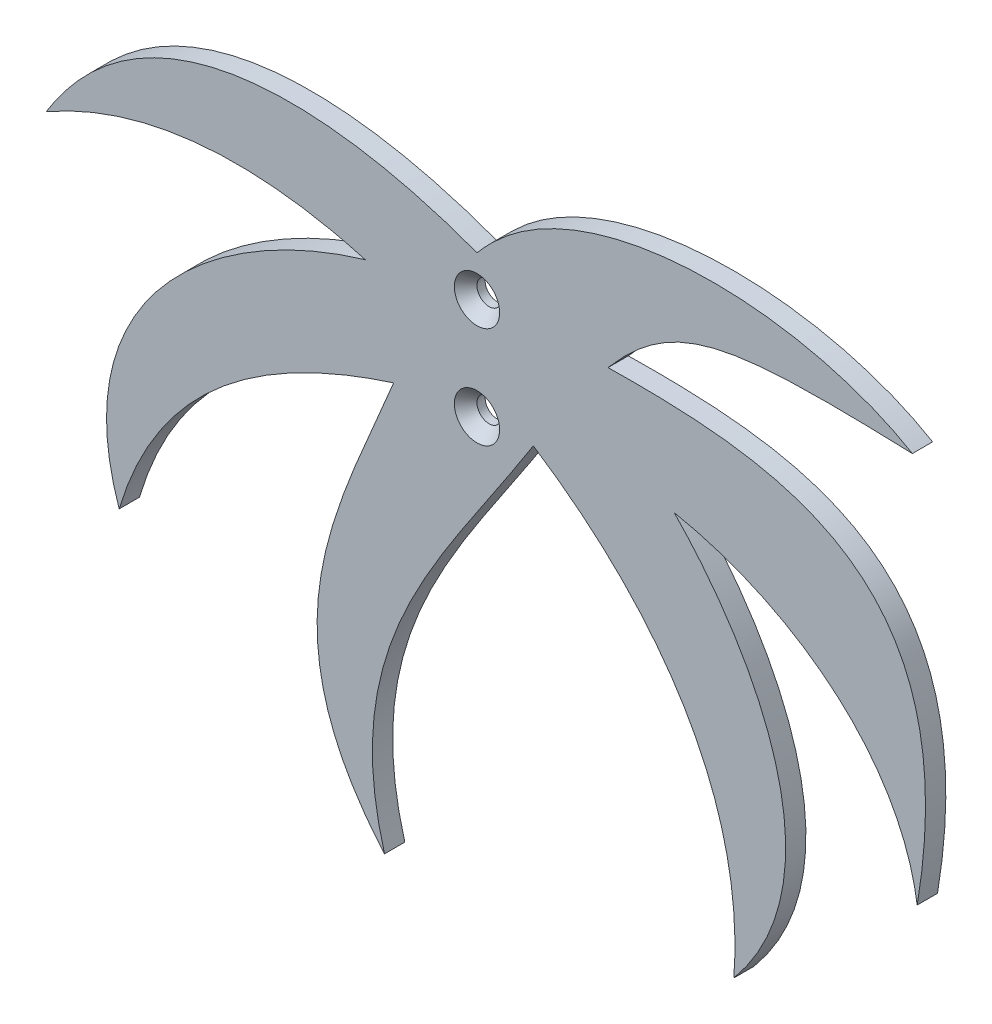
SolidWorks part; units mm, degrees
ref_plane "Front Plane" through (0, 0, 0) normal (0, 0, 1) x (1, 0, 0)
ref_plane "Top Plane" through (0, 0, 0) normal (0, 1, 0) x (1, 0, 0)
ref_plane "Right Plane" through (0, 0, 0) normal (1, 0, 0) x (0, 0, -1)
sketch "Sketch1" plane through (0, 0, 0) normal (0, 0, 1) x (1, 0, 0)
  line L0 (216.6667, 690.5) -> (1083.3333, 690.5) construction
  spline S0 degree 3 poles (34.9319, 165.0254) (48.8281, 187.7197) (76.4544, 188.5201) (100.4458, 180.333) (102.3548, 179.6133) knots 0 0 0 0 0.389678 0.423902 0.423902 0.423902 0.423902
  spline S1 degree 3 poles (34.9319, 165.0254) (50.9354, 174.1809) (68.38, 174.6273) (84.8832, 169.9282) knots 0 0 0 0 0.348653 0.348653 0.348653 0.348653
  spline S2 degree 3 poles (46.3484, 116.89) (37.8919, 141.3966) (59.9186, 161.5978) (82.9281, 169.3503) (84.8832, 169.9282) knots 0 0 0 0 0.348685 0.380913 0.380913 0.380913 0.380913
  spline S3 degree 3 poles (46.3484, 116.89) (52.7964, 138.6162) (70.0851, 149.2983) (89.3085, 155.4556) knots 0 0 0 0 0.378548 0.378548 0.378548 0.378548
  spline S4 degree 3 poles (87.8818, 90.9031) (69.285, 112.2089) (79.6869, 132.5367) (88.8589, 154.3861) (89.3085, 155.4556) knots 0 0 0 0 0.384997 0.404814 0.404814 0.404814 0.404814
  spline S5 degree 3 poles (87.8818, 90.9031) (80.7441, 115.7297) (96.5015, 135.0011) (109.9674, 155.9858) (111.169, 157.8511) knots 0 0 0 0 0.464689 0.510269 0.510269 0.510269 0.510269
  spline S6 degree 3 poles (133.2112, 159.8318) (135.1711, 157.8218) (149.4116, 141.4919) (156.6773, 118.334) (142.5422, 101.4104) knots 0.63299 0.63299 0.63299 0.63299 0.680759 1 1 1 1
  spline S7 degree 3 poles (111.169, 157.8511) (130.2813, 145.4166) (144.4934, 126.3327) (142.5422, 101.4104) knots 0.543056 0.543056 0.543056 0.543056 1 1 1 1
  spline S8 degree 3 poles (102.3548, 179.6133) (103.6883, 181.1888) (120.0852, 197.822) (153.7251, 196.4236) (170.4913, 186.4679) knots 0.566671 0.566671 0.566671 0.566671 0.604774 1 1 1 1
  spline S9 degree 3 poles (133.2112, 159.8318) (133.9795, 159.6828) (151.702, 155.882) (168.6187, 143.5623) (171.2533, 125.6539) knots 0.658819 0.658819 0.658819 0.658819 0.673583 1 1 1 1
  spline S10 degree 3 poles (122.8545, 174.3046) (133.2177, 186.4209) (141.874, 187.4378) (170.4913, 186.4679) knots 0.652056 0.652056 0.652056 0.652056 1 1 1 1
  spline S11 degree 3 poles (122.8545, 174.3046) (150.1009, 174.692) (179.0765, 172.111) (171.2533, 125.6539) knots 0.582619 0.582619 0.582619 0.582619 1 1 1 1
  point P9 (124.3092, 175.9512)
  point P12 (124.3092, 175.9512)
  dimension "D1" = 34.9319
  dimension "D2" = 46.3484
  dimension "D3" = 47.8726
  dimension "D4" = 60.6781
  dimension "D5" = 67.6104
  dimension "D6" = 68.622
  dimension "D7" = 77.8985
  dimension "D8" = 79.0416
  dimension "D9" = 87.8818
  dimension "D10" = 87.958
  dimension "D11" = 89.4821
  dimension "D12" = 84.8832
  dimension "D13" = 96.5482
  dimension "D14" = 89.3085
  dimension "D15" = 102.3548
  dimension "D16" = 107.5434
  dimension "D17" = 106.7052
  dimension "D18" = 111.169
  dimension "D19" = 122.8545
  dimension "D20" = 124.2805
  dimension "D21" = 131.2441
  dimension "D22" = 132.2348
  dimension "D23" = 142.5422
  dimension "D24" = 133.2112
  dimension "D25" = 135.5118
  dimension "D26" = 138.76
  dimension "D27" = 170.4913
  dimension "D28" = 171.2533
  dimension "D29" = 90.9031
  dimension "D30" = 101.4104
  dimension "D31" = 116.89
  dimension "D32" = 121.6149
  dimension "D33" = 123.5201
  dimension "D34" = 125.6539
  dimension "D35" = 150.2543
  dimension "D36" = 151.8203
  dimension "D37" = 142.5721
  dimension "D38" = 145.3918
  dimension "D39" = 152.2505
  dimension "D40" = 163.7087
  dimension "D41" = 128.4849
  dimension "D42" = 138.1521
  dimension "D43" = 153.4552
  dimension "D44" = 165.0254
  dimension "D45" = 167.9494
  dimension "D46" = 155.4556
  dimension "D47" = 172.7543
  dimension "D48" = 157.8511
  dimension "D49" = 159.3379
  dimension "D50" = 181.5964
  dimension "D51" = 183.9745
  dimension "D52" = 186.4679
  dimension "D53" = 159.8318
  dimension "D54" = 690.5
  dimension "D55" = 169.9282
  dimension "D56" = 171.455
  dimension "D57" = 174.3046
  dimension "D58" = 175.9121
  dimension "D59" = 179.6133
  dimension "D60" = 193.6315
extrude "Boss-Extrude1" add sketch "Sketch1" along normal blind 3.175
hole_wizard "CSK for #6 Flat Head Machine Screw1" positions "Sketch2" profile "Sketch3" countersink size "#6" standard "ANSI Inch" end condition through all
sketch "Sketch2" plane through (0, 0, 3.175) normal (0, 0, 1) x (1, 0, 0)
  point P0 (102.3548, 173.2633)
  point P2 (102.3548, 157.3883)
  dimension "D1" = 6.35
  dimension "D2" = 15.875
sketch "Sketch3" plane through (102.3548, 173.2633, 3.175) normal (1, 0, 0) x (0, -1, 0)
  line L0 (0, 0) -> (0, 3.175)
  line L1 (0, 3.175) -> (1.8986, 3.175)
  line L2 (1.8986, 3.175) -> (1.8986, 1.892)
  line L3 (1.8986, 1.892) -> (3.5433, 0)
  line L5 (3.5433, 0) -> (0, 0)
  line L6 (-1.8986, 1.892) -> (-3.5433, 0) construction
  line L11 (0, -6.35) -> (0, 107.95) construction
  dimension "Thru Hole Dia." = 3.7973
  dimension "Thru Hole Depth" = 3.175
  dimension "Near C'Sink Dia." = 7.0866
  dimension "Near C'Sink Angle" = 82
